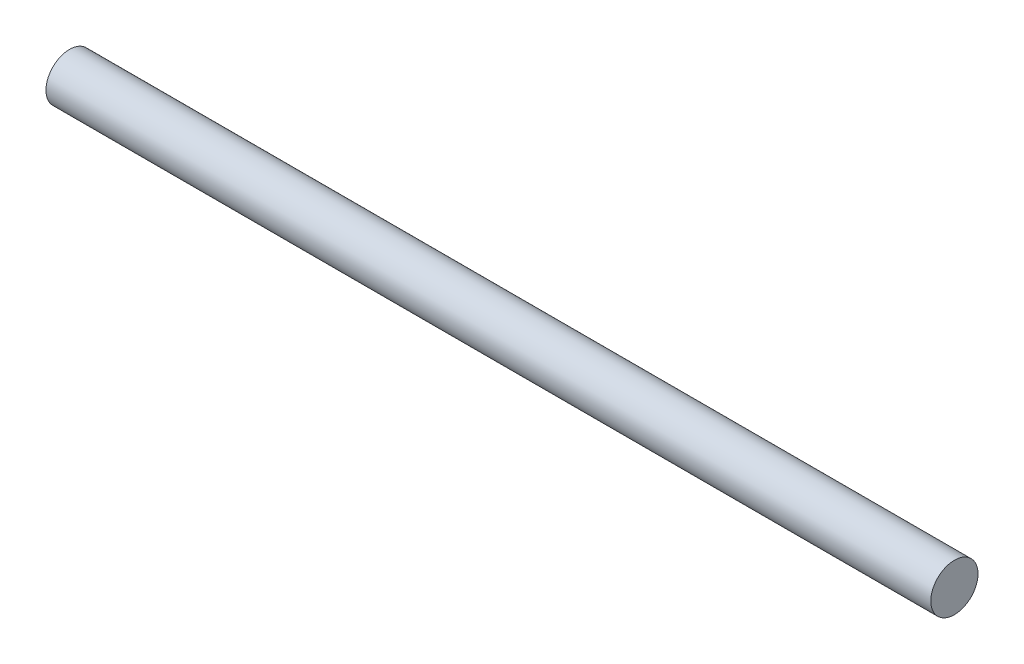
SolidWorks part; units mm, degrees
ref_plane "前视基准面" through (0, 0, 0) normal (0, 0, 1) x (1, 0, 0)
ref_plane "上视基准面" through (0, 0, 0) normal (0, 1, 0) x (1, 0, 0)
ref_plane "右视基准面" through (0, 0, 0) normal (1, 0, 0) x (0, 0, -1)
sketch "草图1" plane through (0, 0, 0) normal (1, 0, 0) x (0, 0, -1)
  circle A0 centre (0, 0) radius 4
  dimension "D1" = 8
extrude "凸台-拉伸1" add sketch "草图1" along normal blind 150
